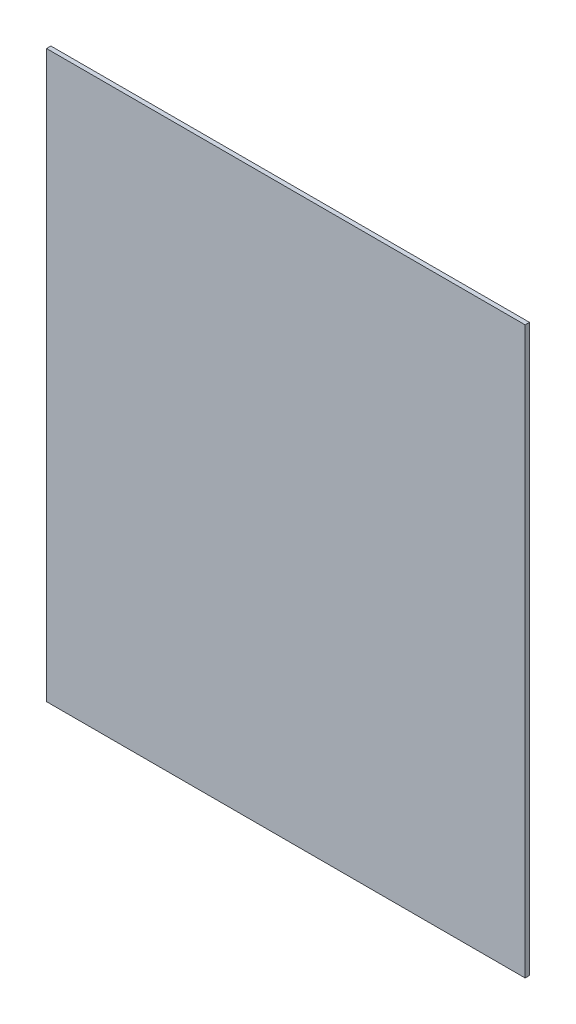
SolidWorks part; units mm, degrees
ref_plane "Front Plane" through (0, 0, 0) normal (0, 0, 1) x (1, 0, 0)
ref_plane "Top Plane" through (0, 0, 0) normal (0, 1, 0) x (1, 0, 0)
ref_plane "Right Plane" through (0, 0, 0) normal (1, 0, 0) x (0, 0, -1)
sketch "Sketch1" plane through (0, 0, 0) normal (0, 0, 1) x (1, 0, 0)
  line L1 (0, 0) -> (330, 0)
  line L2 (0, 0) -> (0, 390)
  line L3 (0, 390) -> (330, 390)
  line L4 (330, 0) -> (330, 390)
  dimension "D1" = 330
  dimension "D2" = 390
extrude "Boss-Extrude1" add sketch "Sketch1" along normal blind 3
